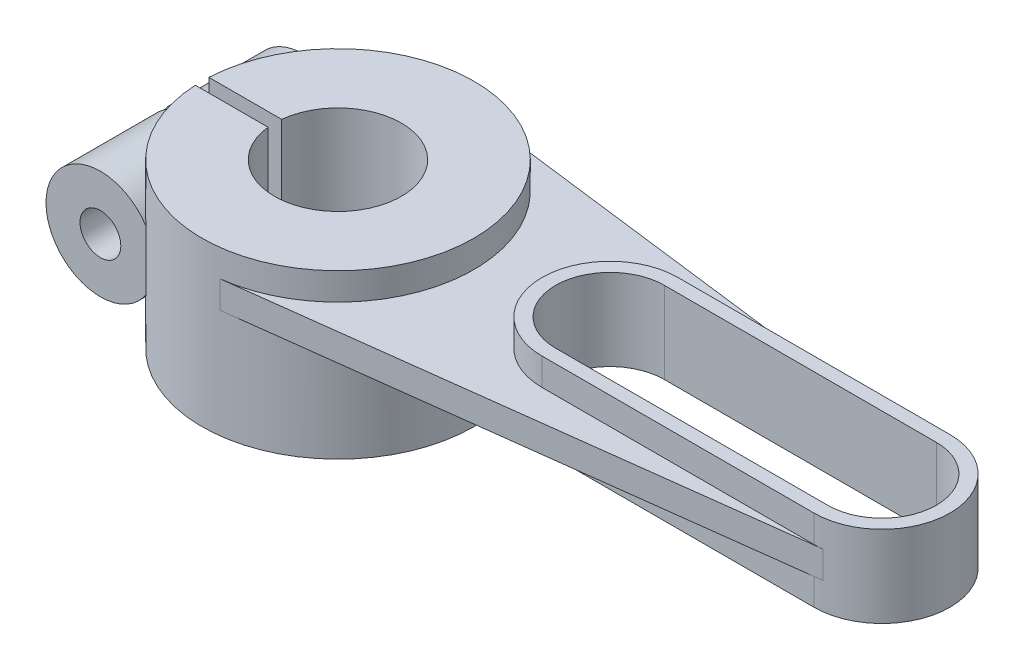
SolidWorks part; units mm, degrees
ref_plane "Front Plane" through (0, 0, 0) normal (0, 0, 1) x (1, 0, 0)
ref_plane "Top Plane" through (0, 0, 0) normal (0, 1, 0) x (1, 0, 0)
ref_plane "Right Plane" through (0, 0, 0) normal (1, 0, 0) x (0, 0, -1)
sketch "Sketch1" plane through (0, 0, 0) normal (0, 1, 0) x (1, 0, 0)
  circle A0 centre (0, 0) radius 30
  circle A1 centre (0, 0) radius 14
  dimension "D1" = 60
  dimension "D2" = 28
extrude "Boss-Extrude1" add sketch "Sketch1" along normal blind 36
ref_plane "Plane1" through (0, 22.4, 0) normal (0, 1, 0) x (1, 0, 0)
sketch "Sketch2" plane through (0, 36, 0) normal (0, 1, 0) x (1, 0, 0)
  line L0 (60, 0) -> (120, 0) construction
  line L1 (60, 15) -> (120, 15)
  line L2 (60, -15) -> (120, -15)
  arc A0 (60, 15) -> (60, -15) centre (60, 0) ccw
  arc A1 (120, -15) -> (120, 15) centre (120, 0) ccw
  point P2 (90, 0)
  dimension "D2" = 15
  dimension "D1" = 60
  dimension "D3" = 60
extrude "Boss-Extrude2" add sketch "Sketch2" against normal blind 18 separate body
sketch "Sketch3" plane through (0, 36, 0) normal (0, 1, 0) x (1, 0, 0)
  line L0 (3.75, -29.7647) -> (121.875, -14.8824)
  line L1 (3.75, 29.7647) -> (121.875, 14.8824)
  circle A0 centre (0, 0) radius 30 construction
  arc A1 (120, -15) -> (120, 15) centre (120, 0) ccw construction
  arc A2 (3.75, -29.7647) -> (3.75, 29.7647) centre (0, 0) ccw
  arc A3 (121.875, -14.8824) -> (121.875, 14.8824) centre (120, 0) ccw
extrude "Boss-Extrude3" add sketch "Sketch3" against normal blind 6 from offset 6 offset against normal yes
sketch "Sketch4" plane through (0, 36, 0) normal (0, 1, 0) x (1, 0, 0)
  line L0 (60, 0) -> (120, 0) construction
  line L1 (60, 12) -> (120, 12)
  line L2 (60, -12) -> (120, -12)
  arc A0 (60, 12) -> (60, -12) centre (60, 0) ccw
  arc A1 (120, -12) -> (120, 12) centre (120, 0) ccw
  point P4 (90, 0)
  dimension "D1" = 12
extrude "Cut-Extrude1" cut sketch "Sketch4" against normal through all
sketch "Sketch5" plane through (0, 0, 0) normal (0, 0, 1) x (1, 0, 0)
  line L0 (-30, 36) -> (-30, 0) construction
  circle A0 centre (-30, 18) radius 12
  dimension "D1" = 24
extrude "Boss-Extrude4" add sketch "Sketch5" along normal mid plane 44.8
sketch "Sketch6" plane through (0, 36, 0) normal (0, 1, 0) x (1, 0, 0)
  line L0 (0, 0) -> (-6.7406, 0) construction
  line L1 (-45, 1.5) -> (-13.9194, 1.5)
  line L2 (-45, 1.5) -> (-45, -1.5)
  line L3 (-45, -1.5) -> (-13.9194, -1.5)
  line L5 (-14, 0) -> (-57.8795, 0) construction
  circle A0 centre (0, 0) radius 14 construction
  arc A1 (-13.9194, 1.5) -> (-13.9194, -1.5) centre (0, 0) ccw
  dimension "D1" = 3
  dimension "D2" = 45
extrude "Cut-Extrude2" cut sketch "Sketch6" against normal through all
hole_wizard "Hole1" positions "Sketch7" profile "Sketch8" legacy end condition through all
sketch "Sketch7" plane through (0, 0, 22.4) normal (0, 0, 1) x (1, 0, 0)
  point P0 (-30, 18)
sketch "Sketch8" plane through (-30, 18, 22.4) normal (1, 0, 0) x (0, -1, 0)
  line L0 (0, 0) -> (0, 52.4)
  line L1 (0, 52.4) -> (4.5, 52.4)
  line L2 (4.5, 52.4) -> (4.5, 0)
  line L3 (4.5, 0) -> (0, 0)
  line L4 (0, 110) -> (0, -10) construction
  dimension "Diameter" = 9
  dimension "Depth" = 52.4
